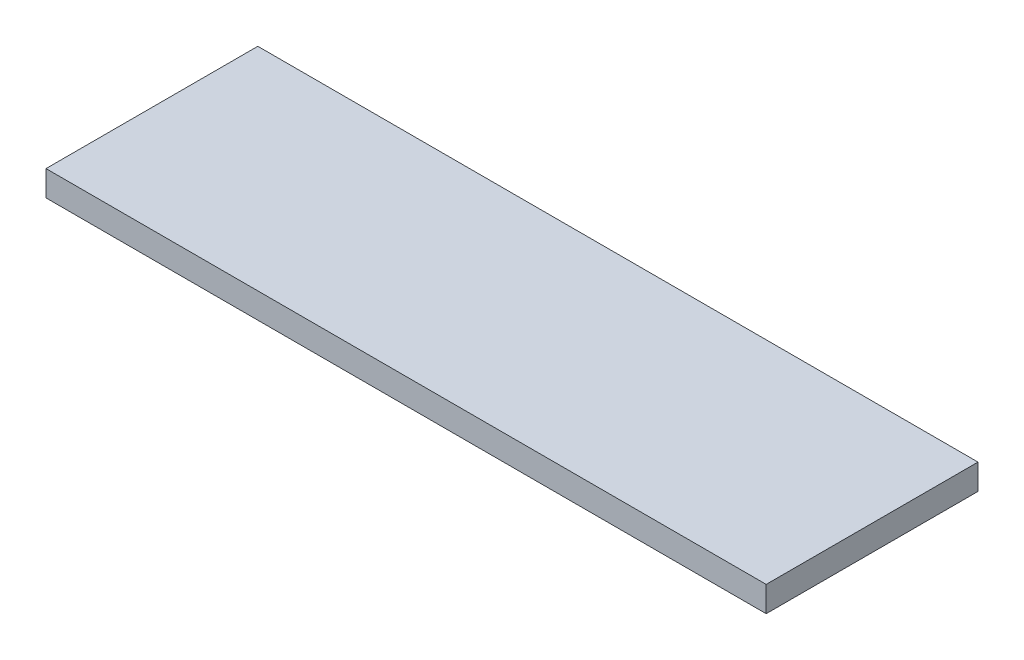
SolidWorks part; units mm, degrees
ref_plane "Front Plane" through (0, 0, 0) normal (0, 0, 1) x (1, 0, 0)
ref_plane "Top Plane" through (0, 0, 0) normal (0, 1, 0) x (1, 0, 0)
ref_plane "Right Plane" through (0, 0, 0) normal (1, 0, 0) x (0, 0, -1)
sketch "Sketch1" plane through (0, 0, 0) normal (0, 0, 1) x (1, 0, 0)
  line L1 (0, 0) -> (85, 0)
  line L2 (0, 0) -> (0, 3)
  line L3 (0, 3) -> (85, 3)
  line L4 (85, 0) -> (85, 3)
  dimension "D1" = 85
  dimension "D2" = 3
extrude "Boss-Extrude1" add sketch "Sketch1" along normal blind 25
